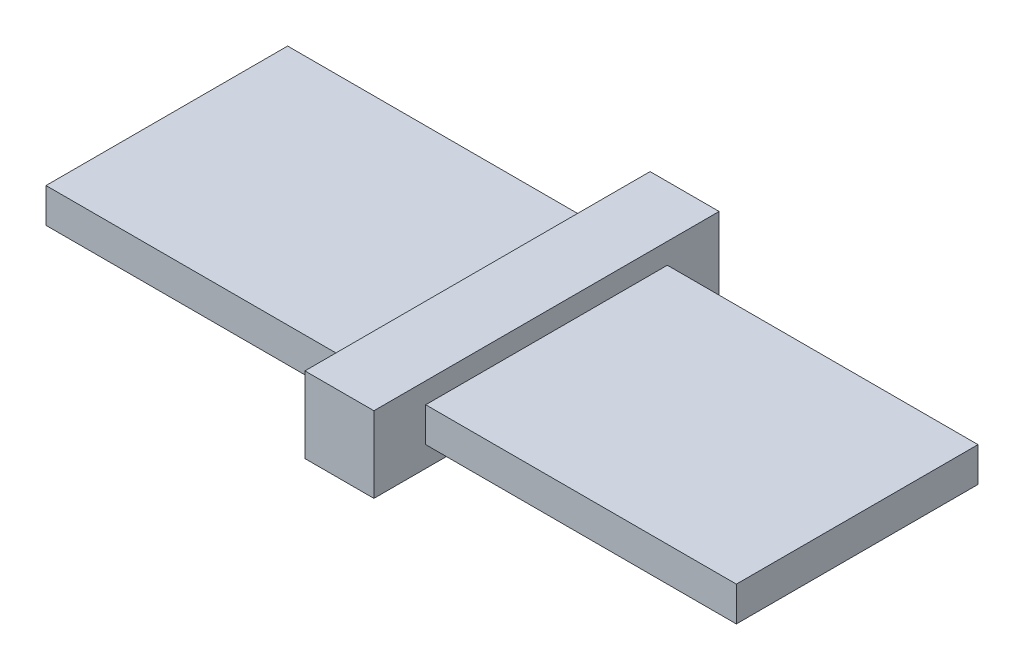
SolidWorks part; units mm, degrees
ref_plane "前视基准面" through (0, 0, 0) normal (0, 0, 1) x (1, 0, 0)
ref_plane "上视基准面" through (0, 0, 0) normal (0, 1, 0) x (1, 0, 0)
ref_plane "右视基准面" through (0, 0, 0) normal (1, 0, 0) x (0, 0, -1)
sketch "草图1" plane through (0, 0, 0) normal (0, 1, 0) x (1, 0, 0)
  line L1 (-50, -17.5) -> (50, -17.5)
  line L2 (-50, -17.5) -> (-50, 17.5)
  line L3 (-50, 17.5) -> (50, 17.5)
  line L4 (50, -17.5) -> (50, 17.5)
  line L5 (-50, -17.5) -> (50, 17.5) construction
  line L6 (-50, 17.5) -> (50, -17.5) construction
  point P0 (0, 0)
  dimension "D1" = 35
  dimension "D2" = 100
extrude "凸台-拉伸1" add sketch "草图1" along normal blind 5
sketch "草图3" plane through (0, 0, 0) normal (1, 0, 0) x (0, 0, -1)
  line L0 (0, 5) -> (0, 0) construction
  line L1 (-17.5, 5) -> (17.5, 5) construction
  line L3 (-25, -3) -> (25, -3)
  line L4 (-25, -3) -> (-25, 8)
  line L5 (-25, 8) -> (25, 8)
  line L6 (25, -3) -> (25, 8)
  line L7 (-25, -3) -> (25, 8) construction
  line L8 (-25, 8) -> (25, -3) construction
  point P5 (0, 2.5)
  dimension "D1" = 3
  dimension "D2" = 50
extrude "凸台-拉伸2" add sketch "草图3" along normal mid plane 10
